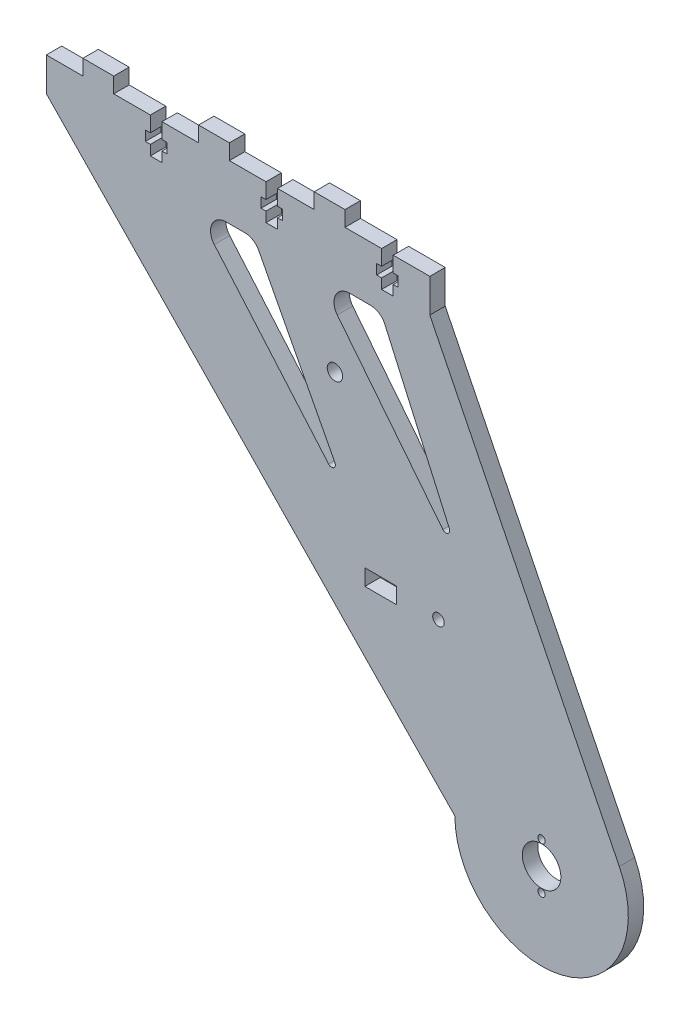
SolidWorks part; units mm, degrees
ref_plane "前视基准面" through (0, 0, 0) normal (0, 0, 1) x (1, 0, 0)
ref_plane "上视基准面" through (0, 0, 0) normal (0, 1, 0) x (1, 0, 0)
ref_plane "右视基准面" through (0, 0, 0) normal (1, 0, 0) x (0, 0, -1)
sketch "草图1" plane through (0, 0, 0) normal (0, 0, 1) x (1, 0, 0)
  line L0 (33.35, -51.75) -> (-20.2627, 32.422) construction
  line L1 (-20.2627, 32.422) -> (-36.65, 58.15) construction
  line L2 (-36.65, 68.25) -> (-36.65, 58.15) construction
  line L15 (-38.15, 66.25) -> (-38.15, 62.25)
  line L16 (-38.15, 62.25) -> (-39.45, 62.25)
  line L17 (-39.45, 62.25) -> (-39.45, 59.65)
  line L18 (-39.45, 59.65) -> (-38.15, 59.65)
  line L19 (-38.15, 59.65) -> (-38.15, 57.05)
  line L20 (-38.15, 57.05) -> (-35.15, 57.05)
  line L21 (-38.15, 66.25) -> (-47.65, 66.25)
  line L22 (-51.65, 66.25) -> (-51.65, 70.25) construction
  line L23 (-47.65, 66.25) -> (-55.65, 66.25) construction
  line L24 (-47.65, 66.25) -> (-47.65, 70.25)
  line L25 (-47.65, 70.25) -> (-55.65, 70.25)
  line L26 (-55.65, 66.25) -> (-55.65, 70.25)
  line L27 (-25.65, 66.25) -> (-17.65, 66.25) construction
  line L28 (-21.65, 66.25) -> (-21.65, 70.25) construction
  line L29 (-17.65, 66.25) -> (-17.65, 70.25)
  line L30 (-25.65, 70.25) -> (-17.65, 70.25)
  line L31 (-25.65, 66.25) -> (-25.65, 70.25)
  line L32 (-35.15, 66.25) -> (-25.65, 66.25)
  line L33 (-35.15, 59.65) -> (-35.15, 57.05)
  line L34 (-33.85, 59.65) -> (-35.15, 59.65)
  line L35 (-33.85, 62.25) -> (-33.85, 59.65)
  line L36 (-35.15, 62.25) -> (-33.85, 62.25)
  line L37 (-35.15, 66.25) -> (-35.15, 62.25)
  line L38 (-95.15, 66.25) -> (-95.15, 57.55)
  line L39 (-95.15, 57.55) -> (10.85, -51.75)
  line L40 (-68.15, 66.25) -> (-68.15, 62.25)
  line L41 (-68.15, 62.25) -> (-69.45, 62.25)
  line L42 (-69.45, 62.25) -> (-69.45, 59.65)
  line L43 (-69.45, 59.65) -> (-68.15, 59.65)
  line L44 (-68.15, 59.65) -> (-68.15, 57.05)
  line L45 (-68.15, 66.25) -> (-77.65, 66.25)
  line L46 (-6.65, 68.25) -> (-6.65, 58.15) construction
  line L49 (-65.15, 57.05) -> (-68.15, 57.05)
  line L50 (-65.15, 59.65) -> (-65.15, 57.05)
  line L51 (-63.85, 59.65) -> (-65.15, 59.65)
  line L52 (-63.85, 62.25) -> (-63.85, 59.65)
  line L53 (-65.15, 62.25) -> (-63.85, 62.25)
  line L54 (-65.15, 66.25) -> (-65.15, 62.25)
  line L55 (-55.65, 66.25) -> (-65.15, 66.25)
  line L58 (-8.15, 66.25) -> (-17.65, 66.25)
  line L59 (-95.15, 66.25) -> (-85.65, 66.25)
  line L60 (-85.65, 66.25) -> (-85.65, 70.25)
  line L61 (-77.65, 70.25) -> (-85.65, 70.25)
  line L62 (-77.65, 66.25) -> (-77.65, 70.25)
  line L63 (4.35, 66.25) -> (4.35, 57.55)
  line L65 (6.5984, -9.75) -> (-8.4016, -9.75) construction
  line L66 (-8.15, 66.25) -> (-8.15, 62.25)
  line L67 (-8.15, 62.25) -> (-9.45, 62.25)
  line L68 (-9.45, 62.25) -> (-9.45, 59.65)
  line L69 (-9.45, 59.65) -> (-8.15, 59.65)
  line L70 (-8.15, 59.65) -> (-8.15, 57.05)
  line L74 (-5.15, 66.25) -> (4.35, 66.25)
  line L75 (-5.15, 57.05) -> (-8.15, 57.05)
  line L76 (-5.15, 59.65) -> (-5.15, 57.05)
  line L77 (-3.85, 59.65) -> (-5.15, 59.65)
  line L78 (-3.85, 62.25) -> (-3.85, 59.65)
  line L79 (-5.15, 62.25) -> (-3.85, 62.25)
  line L80 (-5.15, 66.25) -> (-5.15, 62.25)
  line L81 (-65.15, 57.05) -> (-38.15, 57.05) construction
  line L86 (4.35, 57.55) -> (53.5146, -41.7681)
  line L87 (-12.5016, -11.85) -> (-4.3016, -11.85)
  line L88 (-12.5016, -11.85) -> (-12.5016, -7.65)
  line L89 (-12.5016, -7.65) -> (-4.3016, -7.65)
  line L90 (-4.3016, -11.85) -> (-4.3016, -7.65)
  line L91 (-12.5016, -11.85) -> (-4.3016, -7.65) construction
  line L92 (-12.5016, -7.65) -> (-4.3016, -11.85) construction
  line L93 (-4.3016, -7.65) -> (-38.15, 57.05) construction
  line L94 (-68.15, 57.05) -> (-12.5016, -7.65) construction
  line L95 (-57.2545, 52.05) -> (-41.1771, 52.05)
  line L96 (-16.2141, 4.3341) -> (-41.1771, 52.05)
  line L97 (-16.2141, 4.3341) -> (-16.2141, 4.3341)
  line L98 (-57.2545, 52.05) -> (-16.2141, 4.3341)
  line L99 (-57.2545, 52.05) -> (-57.2545, 52.05)
  line L100 (-35.15, 57.05) -> (-8.15, 57.05) construction
  line L101 (-5.15, 57.05) -> (33.35, -29.25) construction
  line L102 (33.35, -29.25) -> (-35.15, 57.05) construction
  line L103 (12.6564, 4.8633) -> (-24.7977, 52.05)
  line L104 (-24.7977, 52.05) -> (-8.3944, 52.05)
  line L105 (-8.3944, 52.05) -> (-8.3944, 52.05)
  line L106 (-8.3944, 52.05) -> (12.6564, 4.8633)
  circle A0 centre (-36.65, 68.25) radius 1.5 construction
  circle A1 centre (-20.2627, 32.422) radius 2
  circle A2 centre (6.5984, -9.75) radius 1.5
  circle A3 centre (33.35, -51.75) radius 22.5 construction
  arc A6 (10.85, -51.75) -> (53.5146, -41.7681) centre (33.35, -51.75) ccw
  circle A7 centre (33.35, -51.75) radius 5
  circle A8 centre (33.35, -51.75) radius 6 construction
  circle A9 centre (33.35, -45.75) radius 0.95
  circle A10 centre (33.35, -57.75) radius 0.95
  point P39 (-36.65, 57.05)
  point P61 (-66.65, 57.05)
  point P91 (-6.65, 57.05)
  dimension "D17" = 10
  dimension "D18" = 5
  dimension "D1" = 120
  dimension "D2" = 70
  dimension "D3" = 42
  dimension "D4" = 50
  dimension "D5" = 4
  dimension "D6" = 2
  dimension "D7" = 2.6
  dimension "D8" = 2.6
  dimension "D9" = 9.5
  dimension "D10" = 8
  dimension "D11" = 4
  dimension "D12" = 5.6
  dimension "D13" = 8.2
  dimension "D14" = 4.2
  dimension "D15" = 10.1
  dimension "D16" = 15
  dimension "D19" = 5
extrude "凸台-拉伸1" add sketch "草图1" along normal blind 4
sketch "草图2" plane through (0, 66.25, 0) normal (0, 1, 0) x (1, 0, 0)
  line L0 (-68.15, -2) -> (-65.15, -2)
  line L1 (-68.15, -4) -> (-68.15, 0) construction
  line L2 (-65.15, -4) -> (-65.15, 0) construction
  circle A0 centre (-66.65, -2) radius 1.5
fillet "圆角1" radius 4 4 edges at (-8.3944, 52.05, 2) (-24.7977, 52.05, 2) (-41.1771, 52.05, 2) (-57.2545, 52.05, 2)
fillet "圆角2" radius 1 2 edges at (12.6564, 4.8633, 2) (-16.2141, 4.3341, 2)
